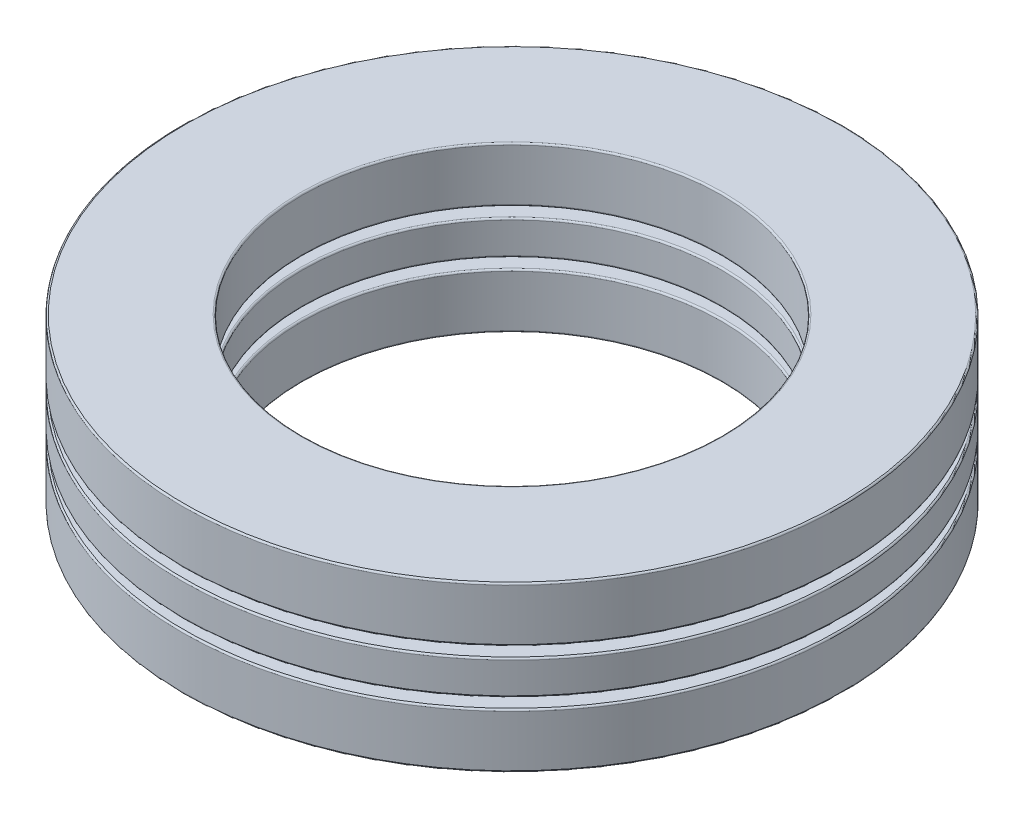
SolidWorks part; units mm, degrees
ref_plane "Front Plane" through (0, 0, 0) normal (0, 0, 1) x (1, 0, 0)
ref_plane "Top Plane" through (0, 0, 0) normal (0, 1, 0) x (1, 0, 0)
ref_plane "Right Plane" through (0, 0, 0) normal (1, 0, 0) x (0, 0, -1)
sketch "Sketch1" plane through (0, 0, 0) normal (1, 0, 0) x (0, 0, -1)
  line L0 (-17.4625, 0) -> (17.4625, 0) construction
  line L1 (0, -4.3434) -> (0, 4.3434) construction
  line L2 (-17.4625, 0.9049) -> (-11.1125, 0.9049)
  line L3 (-17.4625, 0.9049) -> (-17.4625, -0.9049)
  line L4 (-17.4625, -0.9049) -> (-11.1125, -0.9049)
  line L5 (-11.1125, 0.9049) -> (-11.1125, -0.9049)
  line L6 (-14.2875, 1.4478) -> (-14.2875, -1.4478) construction
  circle A0 centre (-14.2875, 0) radius 1.4478 construction
  point P13 (-14.2875, 0.9049)
  dimension "D1" = 2.8956
  dimension "OD" = 34.925
  dimension "Shaft Dia" = 22.225
  dimension "Th" = 8.6868
  dimension "D2" = 1.8098
revolve "Revolve1" add sketch "Sketch1" angle 360 about L1
sketch "Sketch3" plane through (0, 0, 0) normal (1, 0, 0) x (0, 0, -1)
  line L0 (-14.2875, 1.4478) -> (-14.2875, -1.4478)
  arc A0 (-14.2875, 1.4478) -> (-14.2875, -1.4478) centre (-14.2875, 0) ccw
  circle A1 centre (-14.2875, 0) radius 1.4478 construction
revolve "Cut-Revolve1" cut sketch "Sketch3" angle 360 about L0
sketch "Sketch2" plane through (0, 0, 0) normal (1, 0, 0) x (0, 0, -1)
  line L0 (-14.2875, 1.4478) -> (-14.2875, -1.4478)
  arc A0 (-14.2875, 1.4478) -> (-14.2875, -1.4478) centre (-14.2875, 0) ccw
  circle A2 centre (-14.2875, 0) radius 1.4478 construction
revolve "Revolve2" add sketch "Sketch2" angle 360 about L0
ref_axis "Axis1" through (0, 4.3434, 0) along (0, -1, 0)
pattern_circular "CirPattern1" count 7 every 51.429 about axis through (0, 4.3434, 0) along (0, -1, 0) of bodies 187
pattern_circular "CirPattern2" count 7 every 51.429 about axis through (0, 0, 0) along (0, 1, 0) of "Cut-Revolve1"
sketch "Sketch4" plane through (0, 0, 0) normal (1, 0, 0) x (0, 0, -1)
  line L0 (-17.4625, 0.9049) -> (-17.4625, -0.9049) construction
  line L1 (-17.4625, 1.4478) -> (-11.1125, 1.4478)
  line L2 (-17.4625, 1.4478) -> (-17.4625, 4.3434)
  line L3 (-17.4625, 4.3434) -> (-11.1125, 4.3434)
  line L4 (-11.1125, 1.4478) -> (-11.1125, 4.3434)
  line L5 (-17.4625, -4.3434) -> (-11.1125, -4.3434)
  line L6 (-17.4625, -4.3434) -> (-17.4625, -1.4478)
  line L7 (-17.4625, -1.4478) -> (-11.1125, -1.4478)
  line L8 (-11.1125, -4.3434) -> (-11.1125, -1.4478)
  line L9 (-14.2875, 1.4478) -> (-14.2875, -1.4478) construction
  line L10 (-11.1125, 0.9049) -> (-11.1125, -0.9049) construction
  line L11 (0, 0) -> (-17.4625, 0) construction
  line L12 (-17.4625, 0) -> (17.4625, 0) construction
  dimension "Ht" = 8.6868
revolve "Revolve3" add sketch "Sketch4" angle 360 about L1
fillet "Fillet1" radius 0.0869 4 edges at (0, 1.4478, -11.1125) (0, 4.3434, -11.1125) (0, 1.4478, -17.4625) (0, 4.3434, -17.4625)
fillet "Fillet2" radius 0.0869 4 edges at (0, -0.9049, -11.1125) (0, 0.9049, -11.1125) (0, -0.9049, -17.4625) (0, 0.9049, -17.4625)
fillet "Fillet3" radius 0.0869 4 edges at (0, -4.3434, -11.1125) (0, -1.4478, -11.1125) (0, -4.3434, -17.4625) (0, -1.4478, -17.4625)
equation "\"D1@Sketch1\" = \"Th@Sketch1\"/3"
equation "\"D2@Sketch1\" = \"D1@Sketch1\"*.625"
equation "\"Balls@CirPattern1\" = \"OD@Sketch1\"*5"
equation "\"Angle@CirPattern1\" = 360/\"Balls@CirPattern1\""
equation "\"D1@CirPattern2\" = \"Balls@CirPattern1\""
equation "\"D2@CirPattern2\" = \"Angle@CirPattern1\""
equation "\"D1@Fillet1\" = \"Th@Sketch1\"*.01"
equation "\"D1@Fillet2\" = \"D1@Fillet1\""
equation "\"D1@Fillet3\" = \"D1@Fillet1\""
